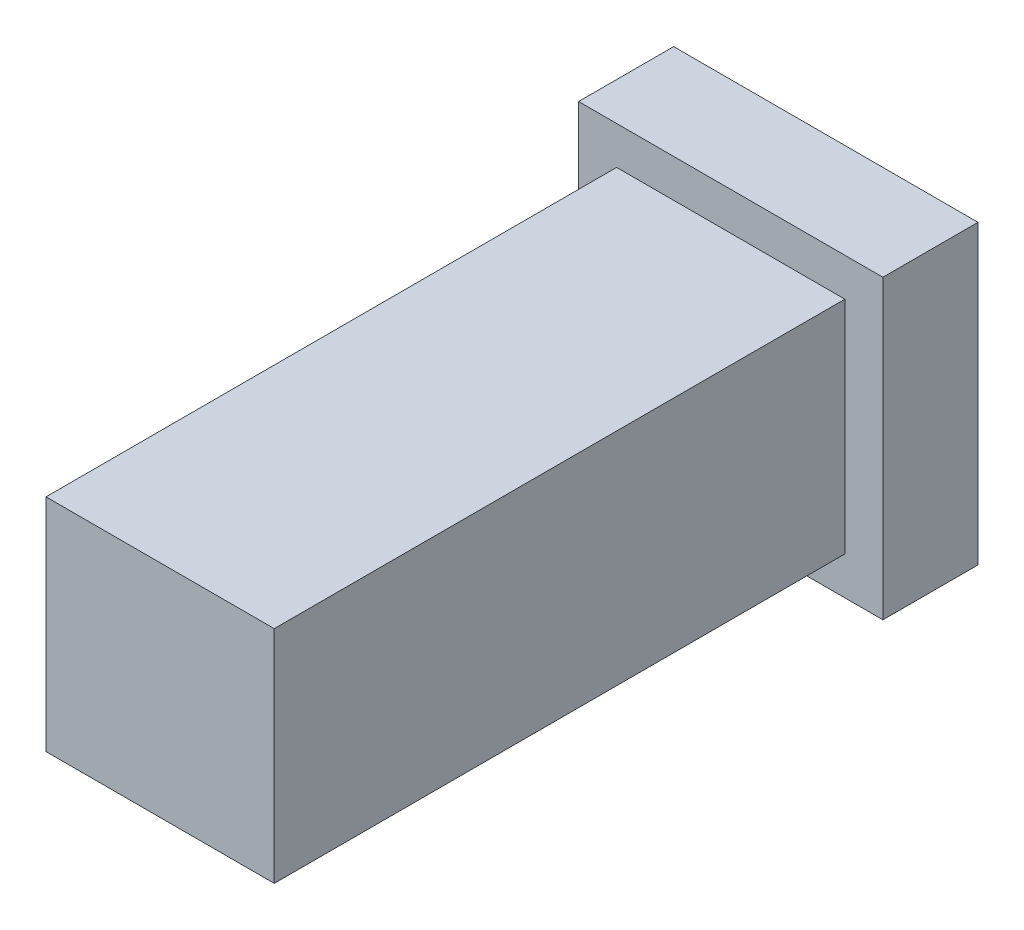
SolidWorks part; units mm, degrees
ref_plane "Front Plane" through (0, 0, 0) normal (0, 0, 1) x (1, 0, 0)
ref_plane "Top Plane" through (0, 0, 0) normal (0, 1, 0) x (1, 0, 0)
ref_plane "Right Plane" through (0, 0, 0) normal (1, 0, 0) x (0, 0, -1)
sketch "Sketch1" plane through (0, 0, 0) normal (0, 0, 1) x (1, 0, 0)
  line L1 (-3, 2.9) -> (3, 2.9)
  line L2 (-3, 2.9) -> (-3, -2.9)
  line L3 (-3, -2.9) -> (3, -2.9)
  line L4 (3, 2.9) -> (3, -2.9)
  line L5 (-3, 2.9) -> (3, -2.9) construction
  line L6 (-3, -2.9) -> (3, 2.9) construction
  point P0 (0, 0)
  dimension "D1" = 6
  dimension "D2" = 5.8
extrude "Boss-Extrude1" add sketch "Sketch1" along normal blind 15
sketch "Sketch2" plane through (0, 0, 0) normal (0, 0, -1) x (-1, 0, 0)
  line L12 (-4, 3.9) -> (-4, -3.9)
  line L13 (-4, -3.9) -> (4, -3.9)
  line L14 (4, -3.9) -> (4, 3.9)
  line L15 (4, 3.9) -> (-4, 3.9)
  line L16 (-4, 3.9) -> (-4, -3.9)
  line L17 (-4, -3.9) -> (4, -3.9)
  line L18 (4, -3.9) -> (4, 3.9)
  line L19 (4, 3.9) -> (-4, 3.9)
  dimension "D1" = 1
extrude "Boss-Extrude2" add sketch "Sketch2" along normal blind 2.5
